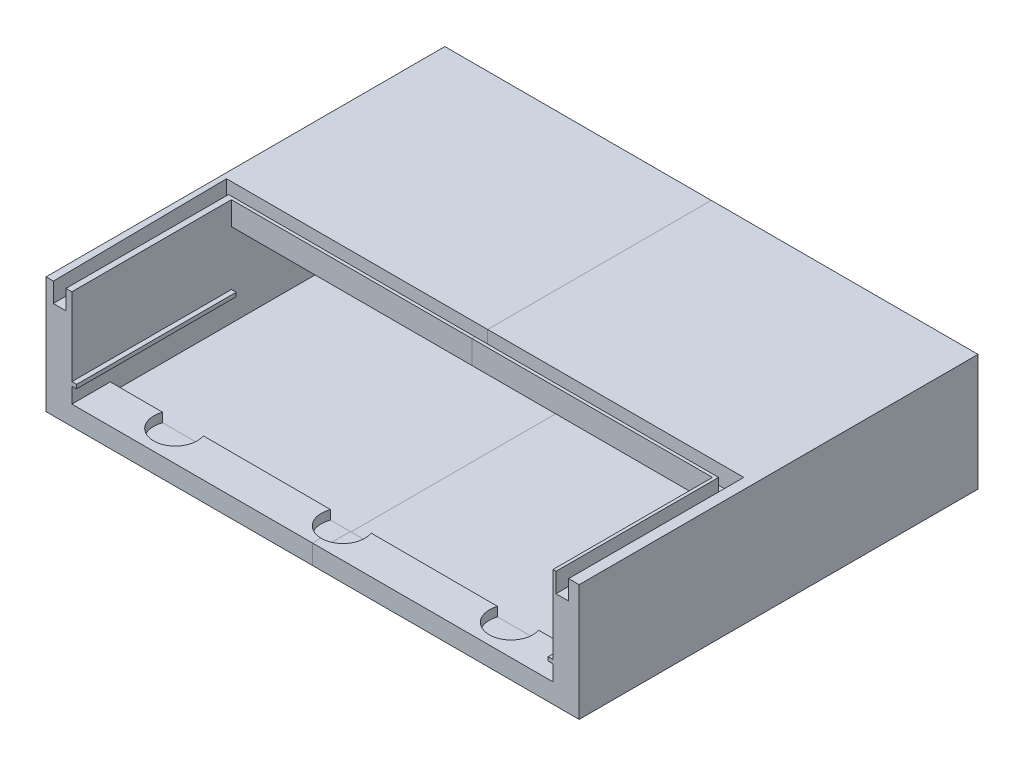
SolidWorks part; units mm, degrees
ref_plane "Front Plane" through (0, 0, 0) normal (0, 0, 1) x (1, 0, 0)
ref_plane "Top Plane" through (0, 0, 0) normal (0, 1, 0) x (1, 0, 0)
ref_plane "Right Plane" through (0, 0, 0) normal (1, 0, 0) x (0, 0, -1)
sketch "Sketch1" plane through (0, 0, 0) normal (0, 1, 0) x (1, 0, 0)
  line L5 (263, -90) -> (0, -90)
  line L6 (0, -90) -> (-5.2977, -90)
  line L7 (-5.2977, -90) -> (-5.2977, 115)
  line L11 (268.7198, 5.6222) -> (268.7198, -90)
  line L12 (268.7198, -90) -> (263, -90)
  line L14 (268.7198, 109.8172) -> (268.7198, 5.6222)
  line L15 (268.7198, 109.8172) -> (268.7198, 5.6222)
  line L16 (-5.2977, 115) -> (268.7198, 115)
  line L17 (268.7198, 115) -> (268.7198, 109.8172)
extrude "Boss-Extrude1" add sketch "Sketch1" along normal blind 60 contours L11 L12 L5 L6 L7 L16 L17 L14
sketch "Sketch4" plane through (0, 60, 0) normal (0, 1, 0) x (1, 0, 0)
  line L0 (-1.5186, -90) -> (4.9814, -90)
  line L1 (-5.2977, -90) -> (268.7198, -90) construction
  line L3 (4.9814, -90) -> (6, -90)
  line L6 (256.8112, -90) -> (263.3112, -90)
  line L7 (263.3112, -90) -> (263.3112, 0.0612)
  line L8 (-1.5186, -90) -> (-2.5678, 0.0612)
  line L9 (-5.2977, -90) -> (268.7198, -90) construction
  line L11 (-2.5678, 0.0612) -> (-2.5087, -5.0156)
  line L12 (4.9814, -6.4388) -> (256.8112, -6.4388)
  line L13 (256.8112, -6.4388) -> (256.8112, -90)
  line L14 (4.9814, -6.4388) -> (4.9814, -90)
  line L15 (-2.5678, 0.0612) -> (263.3112, 0.0612)
  line L16 (256.8112, -90) -> (258.4102, -90)
  line L17 (256.8112, -90) -> (256.8523, -90)
  dimension "D1" = 6.5
  dimension "D2" = 6.5
  dimension "D3" = 6.5
extrude "Cut-Extrude1" cut sketch "Sketch4" against normal blind 10 contours L8 L0 L14 L12 L13 L6 L7 L15
sketch "Sketch5" plane through (0, 60, 0) normal (0, 1, 0) x (1, 0, 0)
  line L0 (8, -90) -> (255.25, -90)
  line L3 (8, -8) -> (8, -90)
  line L4 (4.9814, -90) -> (256.8112, -90) construction
  line L7 (255.25, -8) -> (8, -8)
  line L8 (255.25, -8) -> (255.25, -90)
extrude "Cut-Extrude2" cut sketch "Sketch5" against normal blind 50
sketch "Sketch6" plane through (0, 10, 0) normal (0, 1, 0) x (1, 0, 0)
  line L0 (45.2232, -85.5432) -> (0.227, -85.5432) construction
  line L2 (45.2232, -85.5432) -> (45.2232, -90.0432) construction
  line L4 (45.2232, -85.5432) -> (131.2792, -85.5407) construction
  line L5 (131.7324, -85.5432) -> (218.2417, -85.5432) construction
  line L6 (218.2417, -85.5432) -> (218.2417, -90.0432) construction
  line L7 (131.7324, -85.5432) -> (131.7324, -90.0432) construction
  line L8 (45.2232, -85.5432) -> (45.2232, -58.4326) construction
  line L9 (131.7324, -85.5432) -> (131.7324, -57.0319) construction
  line L10 (218.2417, -85.5432) -> (218.2417, -57.6944) construction
  circle A2 centre (131.8578, -74.5221) radius 11.15
  circle A3 centre (45.4096, -74.2249) radius 11.15
  circle A4 centre (217.9835, -74.2641) radius 11.15
  dimension "D2" = 22.3
  dimension "D3" = 22.3
  dimension "D4" = 22.3
extrude "Cut-Extrude3" cut sketch "Sketch6" against normal blind 4.66
sketch "Sketch7" plane through (0, 10, 0) normal (0, 1, 0) x (1, 0, 0)
  line L1 (8, -8) -> (8, -90) construction
  line L2 (8, -70.253) -> (8, 98.9628)
  line L3 (8, 98.9628) -> (255.25, 98.9628)
  line L4 (255.25, 98.9628) -> (255.25, -70.7173)
  line L5 (255.25, -90) -> (255.25, -8) construction
  line L7 (8, -70.253) -> (255.25, -70.7173)
extrude "Cut-Extrude4" cut sketch "Sketch7" against normal blind 5
sketch "Sketch9" plane through (0, 0, 90) normal (0, 0, 1) x (1, 0, 0)
  line L6 (8, 10) -> (8, 60) construction
  line L7 (8, 20) -> (10.4282, 20)
  line L8 (10.4282, 20) -> (10.4282, 18)
  line L9 (10.4282, 18) -> (8, 18)
  line L10 (8, 18) -> (8, 20)
sketch "Sketch10" plane through (0, 10, 0) normal (0, 1, 0) x (1, 0, 0)
  line L0 (131.625, -90) -> (131.625, -8) construction
  line L1 (8, -90) -> (255.25, -90) construction
  line L2 (255.25, -8) -> (8, -8) construction
extrude "Boss-Extrude3" add sketch "Sketch9" against normal blind 85
ref_plane "Plane1" through (131.625, 0, 0) normal (1, 0, 0) x (0, 0, -1)
mirror "Mirror1" about plane through (131.625, 0, 0) normal (1, 0, 0) of "Boss-Extrude3"
sketch "Sketch11" plane through (0, 0, 8) normal (0, 0, 1) x (1, 0, 0)
  line L1 (8, 10) -> (255.25, 10)
  line L4 (255.25, 10) -> (255.25, 48)
  line L11 (255.25, 20) -> (255.25, 60) construction
  line L12 (255.25, 48) -> (8, 48)
  line L13 (8, 20) -> (8, 60) construction
  line L14 (8, 48) -> (8, 10)
extrude "Cut-Extrude6" cut sketch "Sketch11" against normal blind 109 contours L14 L1 L4 L12
sketch "Sketch17" plane through (0, 0, -101) normal (0, 0, 1) x (1, 0, 0)
  line L0 (131.625, 59.9508) -> (131.625, -0.0544) construction
  line L1 (131.625, 38.021) -> (131.625, 59.9508)
  line L5 (142.9964, 44.5863) -> (131.625, 38.021)
  line L7 (142.9964, 44.5863) -> (142.9964, 18.0144)
  line L8 (142.9964, 18.0144) -> (131.625, 24.5797)
  line L9 (-5.2977, 0) -> (131.625, -0.0544)
  line L15 (131.625, -0.0544) -> (131.625, 24.5797)
  line L16 (-5.2977, 0) -> (-5.2977, 64.274)
  line L17 (-5.2977, 64.274) -> (131.625, 64.274)
  line L18 (131.625, -103.9295) -> (131.625, 103.9295) construction
  line L19 (131.625, 64.274) -> (131.625, 59.9508)
split "Split3" trim tools "Sketch17" bodies to split 111 resulting bodies 116 117
split "Split4" trim tools "Sketch17" bodies to split 116 117 resulting bodies 118 119
